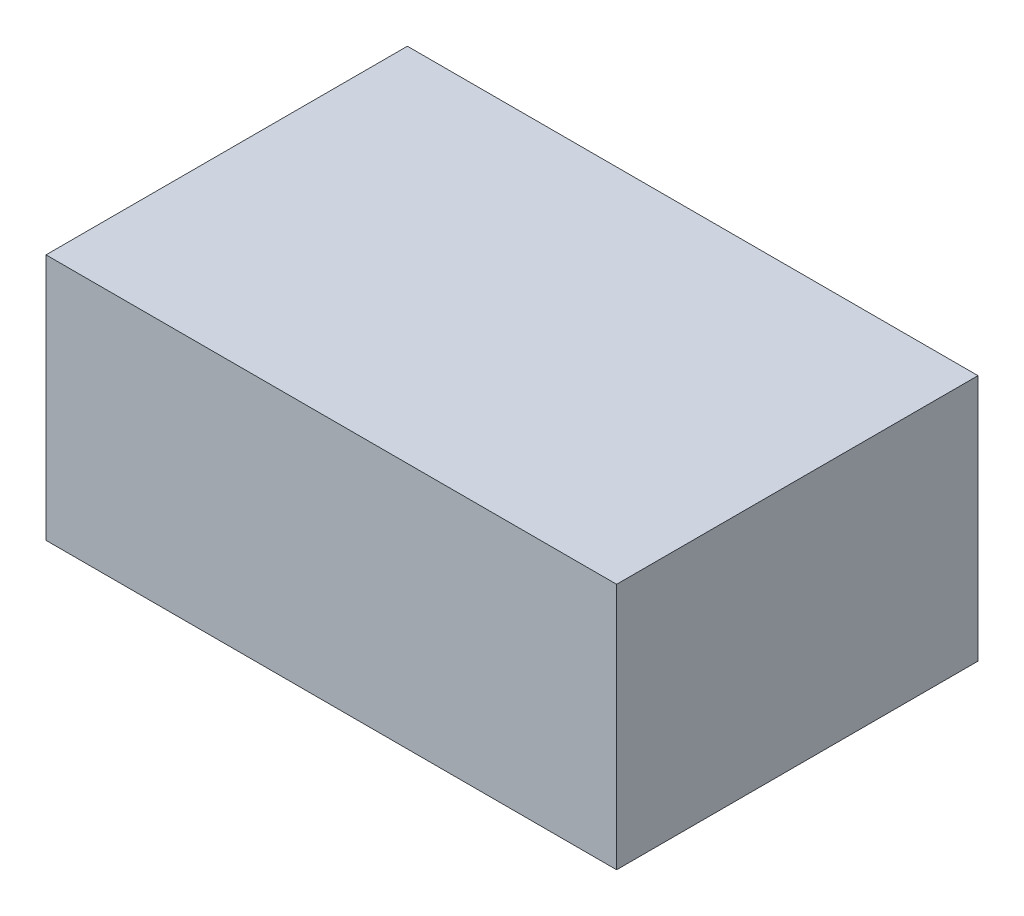
SolidWorks part; units mm, degrees
ref_plane "前视基准面" through (0, 0, 0) normal (0, 0, 1) x (1, 0, 0)
ref_plane "上视基准面" through (0, 0, 0) normal (0, 1, 0) x (1, 0, 0)
ref_plane "右视基准面" through (0, 0, 0) normal (1, 0, 0) x (0, 0, -1)
sketch "草图1" plane through (0, 0, 0) normal (0, 0, 1) x (1, 0, 0)
  line L0 (-101.2013, 0) -> (115.6222, 0) construction
  line L1 (-75, 32.5) -> (75, 32.5)
  line L2 (-75, 32.5) -> (-75, -32.5)
  line L3 (-75, -32.5) -> (75, -32.5)
  line L4 (75, 32.5) -> (75, -32.5)
  line L5 (0, 88.9082) -> (0, -50.2815) construction
  dimension "D1" = 150
  dimension "D2" = 65
extrude "拉伸1" add sketch "草图1" along normal blind 95
sketch "草图2" plane through (0, 0, 0) normal (0, 0, -1) x (-1, 0, 0)
  line L0 (-75, 32.5) -> (75, 32.5) construction
  line L1 (59, 25.5) -> (60, 25.5)
  line L2 (59, 25.5) -> (59, 18.5)
  line L3 (59, 18.5) -> (60, 18.5)
  line L4 (60, 25.5) -> (60, 18.5)
  line L5 (75, 32.5) -> (75, -32.5) construction
  dimension "D1" = 7
  dimension "D2" = 15
  dimension "D3" = 7
  dimension "D4" = 1
ref_plane "基准面1" through (0, 19, 0) normal (0, 1, 0) x (-1, 0, 0)
sketch "草图3" plane through (0, 19, 0) normal (0, 1, 0) x (-1, 0, 0)
  line L0 (59.5, 0) -> (59.5, -4)
  line L1 (59, 0) -> (60, 0) construction
  line L2 (59.5, -4) -> (48.5, -4)
  dimension "D1" = 11
  dimension "D2" = 4
sweep "扫描1" add profiles "草图2" path "草图3"
ref_plane "基准面2" through (0, 0, 0) normal (0, 1, 0) x (-1, 0, 0)
mirror "镜向1" about plane through (0, 0, 0) normal (0, 1, 0) of "扫描1"
